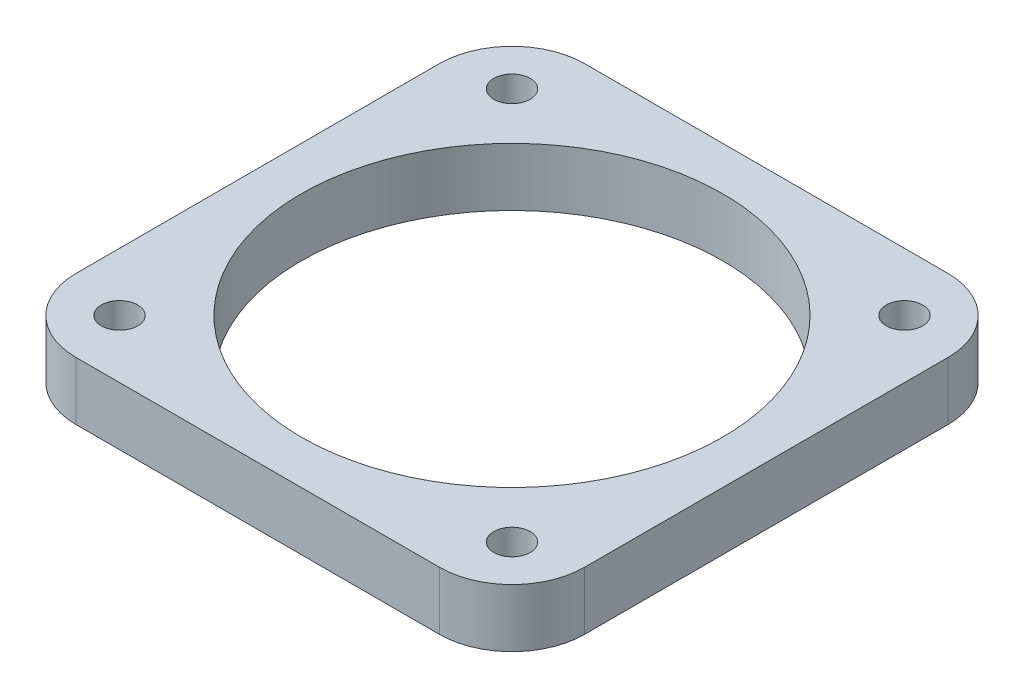
SolidWorks part; units mm, degrees
ref_plane "Alzado" through (0, 0, 0) normal (0, 0, 1) x (1, 0, 0)
ref_plane "Planta" through (0, 0, 0) normal (0, 1, 0) x (1, 0, 0)
ref_plane "Vista lateral" through (0, 0, 0) normal (1, 0, 0) x (0, 0, -1)
sketch "Croquis1" plane through (0, 0, 0) normal (0, 1, 0) x (1, 0, 0)
  line L5 (-35, 35) -> (35, 35)
  line L6 (-35, 35) -> (-35, -35)
  line L7 (-35, -35) -> (35, -35)
  line L8 (35, 35) -> (35, -35)
  line L9 (-35, 35) -> (35, -35) construction
  line L10 (-35, -35) -> (35, 35) construction
  circle A0 centre (0, 0) radius 35
  circle A1 centre (0, 0) radius 29
  dimension "D1" = 58
  dimension "D2" = 70
  dimension "D3" = 70
extrude "Saliente-Extruir1" add sketch "Croquis1" along normal blind 8 contours A0 A1 | A0 L6 L7 | A0 L7 L8 | A0 L8 L5 | A0 L5 L6
fillet "Redondeo1" radius 10 4 edges at (-35, 4, 35) (-35, 4, -35) (35, 4, -35) (35, 4, 35)
sketch "Croquis2" plane through (0, 8, 0) normal (0, 1, 0) x (1, 0, 0)
  line L0 (-35, 25) -> (-35, -25) construction
  line L1 (-25, 35) -> (25, 35) construction
  line L2 (35, 25) -> (35, -25) construction
  line L3 (-25, -35) -> (25, -35) construction
  circle A0 centre (-27, 27) radius 2.5
  circle A1 centre (27, 27) radius 2.5
  circle A2 centre (27, -27) radius 2.5
  circle A3 centre (-27, -27) radius 2.5
  point P12 (0, 0)
  point P15 (0, 0)
  dimension "D1" = 5
  dimension "D2" = 5
  dimension "D3" = 5
  dimension "D4" = 5
  dimension "D5" = 8
  dimension "D6" = 8
  dimension "D7" = 8
  dimension "D8" = 8
  dimension "D9" = 8
  dimension "D10" = 8
  dimension "D11" = 8
  dimension "D12" = 8
extrude "Cortar-Extruir1" cut sketch "Croquis2" against normal blind 10
equation "\"position\"= 8"
equation "\"radio\" = 5"
equation "\"D1@Croquis2\"=\"radio\""
equation "\"D2@Croquis2\"=\"radio\""
equation "\"D3@Croquis2\"=\"radio\""
equation "\"D4@Croquis2\"=\"radio\""
equation "\"D5@Croquis2\"=\"position\""
equation "\"D6@Croquis2\"=\"position\""
equation "\"D7@Croquis2\"=\"position\""
equation "\"D8@Croquis2\"=\"position\""
equation "\"D9@Croquis2\"=\"position\""
equation "\"D10@Croquis2\"=\"position\""
equation "\"D11@Croquis2\"=\"position\""
equation "\"D12@Croquis2\"=\"position\""
